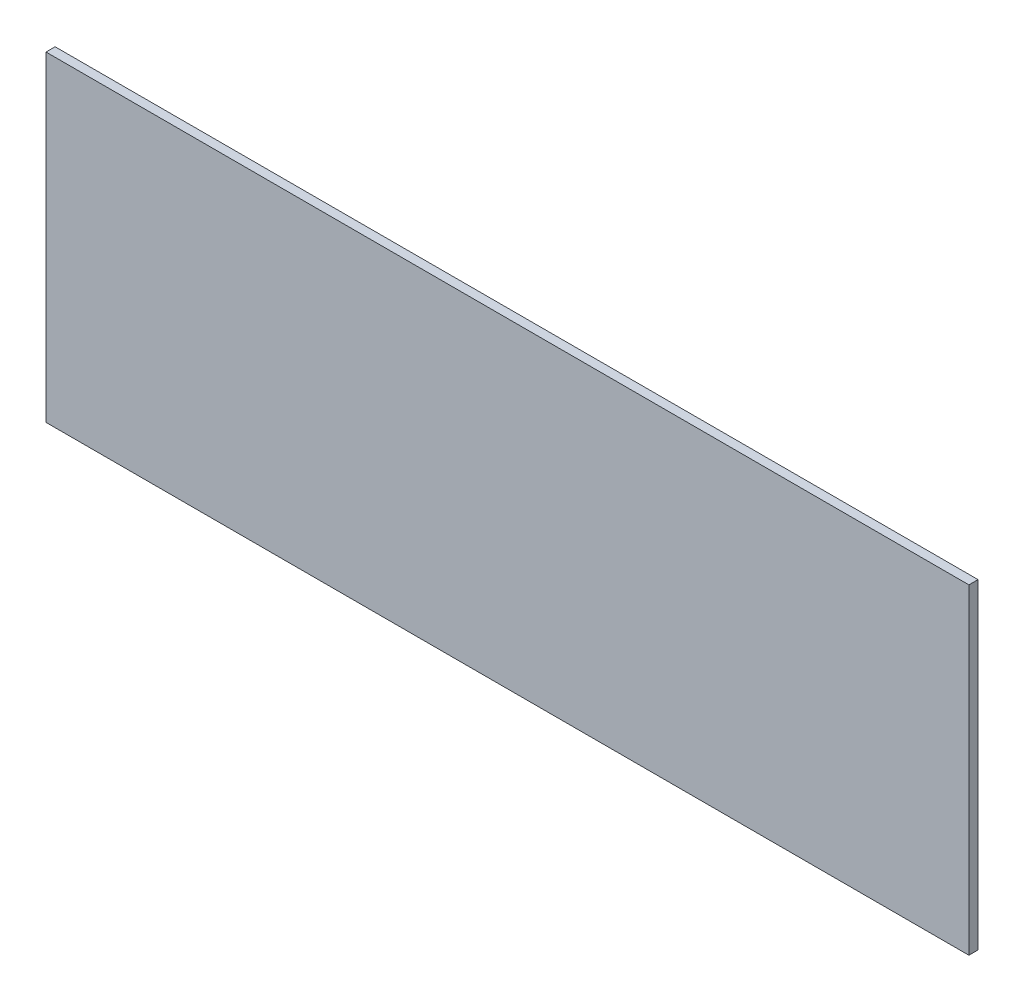
SolidWorks part; units mm, degrees
material "E-Glass Fiber"
ref_plane "Front Plane" through (0, 0, 0) normal (0, 0, 1) x (1, 0, 0)
ref_plane "Top Plane" through (0, 0, 0) normal (0, 1, 0) x (1, 0, 0)
ref_plane "Right Plane" through (0, 0, 0) normal (1, 0, 0) x (0, 0, -1)
sketch "Sketch1" plane through (0, 0, 0) normal (0, 0, 1) x (1, 0, 0)
  line L1 (-120.65, -41.9354) -> (120.65, -41.9354)
  line L2 (-120.65, -41.9354) -> (-120.65, 41.9354)
  line L3 (-120.65, 41.9354) -> (120.65, 41.9354)
  line L4 (120.65, -41.9354) -> (120.65, 41.9354)
  line L5 (-120.65, -41.9354) -> (120.65, 41.9354) construction
  line L6 (-120.65, 41.9354) -> (120.65, -41.9354) construction
  point P0 (0, 0)
  dimension "D1" = 241.3
  dimension "D2" = 83.8708
extrude "Boss-Extrude1" add sketch "Sketch1" along normal blind 2.3813
